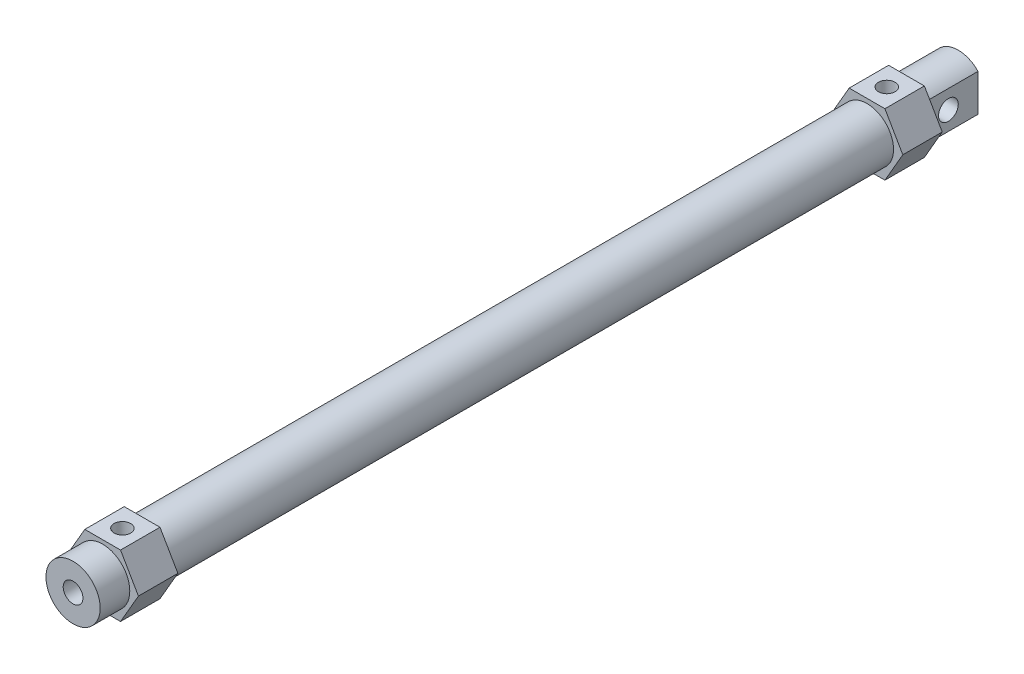
SolidWorks part; units mm, degrees
material "6061 合金"
ref_plane "前视基准面" through (0, 0, 0) normal (0, 0, 1) x (1, 0, 0)
ref_plane "上视基准面" through (0, 0, 0) normal (0, 1, 0) x (1, 0, 0)
ref_plane "右视基准面" through (0, 0, 0) normal (1, 0, 0) x (0, 0, -1)
sketch "草图1" plane through (0, 0, 0) normal (0, 0, 1) x (1, 0, 0)
  line L0 (0, 0) -> (29, 0) construction
  line L2 (14.5, 0) -> (7.25, 12.5574)
  line L3 (7.25, 12.5574) -> (-7.25, 12.5574)
  line L4 (-7.25, 12.5574) -> (-14.5, 0)
  line L5 (-14.5, 0) -> (-7.25, -12.5574)
  line L6 (-7.25, -12.5574) -> (7.25, -12.5574)
  line L7 (7.25, -12.5574) -> (14.5, 0)
  circle A0 centre (0, 0) radius 12.5574 construction
  dimension "D1" = 29
extrude "凸台-拉伸1" add sketch "草图1" along normal blind 16
sketch "草图3" plane through (0, 0, 16) normal (0, 0, 1) x (1, 0, 0)
  line L6 (7.25, -12.5574) -> (14.5, 0)
  line L7 (-7.25, -12.5574) -> (7.25, -12.5574)
  line L8 (-14.5, 0) -> (-7.25, -12.5574)
  line L9 (-7.25, 12.5574) -> (-14.5, 0)
  line L10 (7.25, 12.5574) -> (-7.25, 12.5574)
  line L11 (14.5, 0) -> (7.25, 12.5574)
  line L12 (7.25, -12.5574) -> (14.5, 0)
  line L13 (-7.25, -12.5574) -> (7.25, -12.5574)
  line L14 (-14.5, 0) -> (-7.25, -12.5574)
  line L15 (-7.25, 12.5574) -> (-14.5, 0)
  line L16 (7.25, 12.5574) -> (-7.25, 12.5574)
  line L17 (14.5, 0) -> (7.25, 12.5574)
  circle A0 centre (0, 0) radius 10.75
  circle A1 centre (0, 0) radius 10
  dimension "D2" = 20
  dimension "D3" = 21.5
  dimension "D1" = 0
extrude "凸台-拉伸3" add sketch "草图3" along normal blind 294 contours A0 A1
sketch "草图4" plane through (0, 0, 310) normal (0, 0, 1) x (1, 0, 0)
  line L0 (0, 0) -> (14.5, 0) construction
  line L1 (14.5, 0) -> (7.25, 12.5574)
  line L2 (7.25, 12.5574) -> (-7.25, 12.5574)
  line L3 (-7.25, 12.5574) -> (-14.5, 0)
  line L4 (-14.5, 0) -> (-7.25, -12.5574)
  line L5 (-7.25, -12.5574) -> (7.25, -12.5574)
  line L6 (7.25, -12.5574) -> (14.5, 0)
  circle A0 centre (0, 0) radius 12.5574 construction
  dimension "D1" = 29
extrude "凸台-拉伸4" add sketch "草图4" along normal blind 16
sketch "草图5" plane through (0, 12.5574, 0) normal (0, 1, 0) x (1, 0, 0)
  line L0 (0, -326) -> (0, 0) construction
  line L1 (7.25, -326) -> (-7.25, -326) construction
  line L2 (7.25, 0) -> (-7.25, 0) construction
  point P5 (0, -318)
  point P6 (0, -8)
  dimension "D1" = 8
  dimension "D2" = 8
hole_wizard "1/8 Rc 螺纹孔1" positions "3D草图1" profile "草图6" size "1/8" standard "GB"
sketch3d "3D草图1"
  point P0 (0, 12.5574, 318)
  point P3 (0, 12.5574, 8)
sketch "草图6" plane through (0, 12.5574, 318) normal (1, 0, 0) x (0, 0, 1)
  line L0 (0, 0) -> (0, 17.8494)
  line L1 (3.95, 14.535) -> (0, 17.8494)
  line L2 (-3.95, 14.535) -> (0, 17.8494) construction
  line L3 (3.95, 14.535) -> (3.95, 10)
  line L4 (3.95, 10) -> (3.052, 10)
  line L5 (3.052, 10) -> (3.3642, 0)
  line L6 (-3.052, 10) -> (-3.3642, 0) construction
  line L7 (3.3642, 0) -> (0, 0)
  line L8 (0, -6.35) -> (0, 107.95) construction
  line L11 (-3.95, 10) -> (-3.052, 10) construction
  dimension "螺纹孔钻头直径" = 7.9
  dimension "螺纹孔钻头深度" = 14.535
  dimension "螺纹直径" = 6.7283
  dimension "螺纹角度" = 3.576
  dimension "螺纹深度" = 10
  dimension "导头角度" = 100
sketch "草图8" plane through (0, 0, 326) normal (0, 0, 1) x (1, 0, 0)
  circle A0 centre (0, 0) radius 11
  dimension "D1" = 22
extrude "凸台-拉伸5" add sketch "草图8" along normal blind 12
cosmetic thread "装饰螺纹线1" parameters "D2"=21
sketch "草图9" plane through (0, 0, 338) normal (0, 0, 1) x (1, 0, 0)
  circle A0 centre (0, 0) radius 4
  dimension "D1" = 8
extrude "切除-拉伸1" cut sketch "草图9" against normal blind 50
sketch "草图10" plane through (0, 0, 0) normal (0, 0, -1) x (-1, 0, 0)
  circle A0 centre (0, 0) radius 11
  dimension "D1" = 22
extrude "凸台-拉伸6" add sketch "草图10" along normal blind 21
cosmetic thread "装饰螺纹线2" parameters "D2"=21
cosmetic thread "装饰螺纹线3" parameters "D2"=21
sketch "草图11" plane through (0, 0, -21) normal (0, 0, -1) x (-1, 0, 0)
  line L1 (8, 15) -> (-8, 15)
  line L2 (8, 15) -> (8, -15)
  line L3 (8, -15) -> (-8, -15)
  line L4 (-8, 15) -> (-8, -15)
  line L5 (8, 15) -> (-8, -15) construction
  line L6 (8, -15) -> (-8, 15) construction
  circle A0 centre (0, 0) radius 22.5
  point P0 (0, 0)
  dimension "D1" = 16
  dimension "D3" = 45
  dimension "D2" = 30
extrude "切除-拉伸2" cut sketch "草图11" against normal up to surface (21 mm away) up to face at (-11, 0, 0)
sketch "草图12" plane through (-8, 0, 0) normal (-1, 0, 0) x (0, 0, 1)
  line L0 (-21, 0) -> (0, 0) construction
  line L1 (-21, -7.5498) -> (-21, 7.5498) construction
  circle A0 centre (-9, 0) radius 4
  dimension "D1" = 8
  dimension "D2" = 12
extrude "切除-拉伸3" cut sketch "草图12" against normal through all
